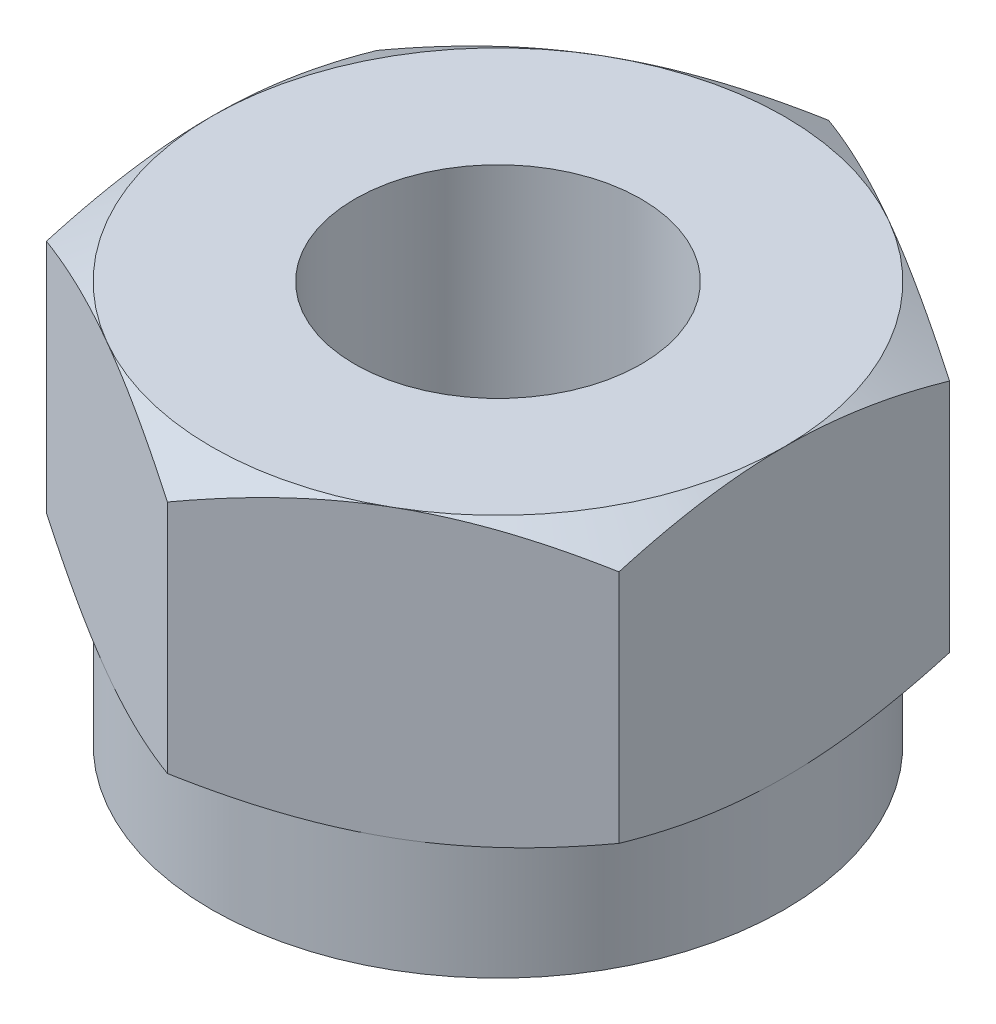
SolidWorks part; units mm, degrees
material "AISI 304"
ref_plane "前视基准面" through (0, 0, 0) normal (0, 0, 1) x (1, 0, 0)
ref_plane "上视基准面" through (0, 0, 0) normal (0, 1, 0) x (1, 0, 0)
ref_plane "右视基准面" through (0, 0, 0) normal (1, 0, 0) x (0, 0, -1)
sketch "草图1" plane through (0, 0, 0) normal (0, 1, 0) x (1, 0, 0)
  line L1 (2, 1.1547) -> (0, 2.3094)
  line L2 (0, 2.3094) -> (-2, 1.1547)
  line L3 (-2, 1.1547) -> (-2, -1.1547)
  line L4 (-2, -1.1547) -> (0, -2.3094)
  line L5 (0, -2.3094) -> (2, -1.1547)
  line L6 (2, -1.1547) -> (2, 1.1547)
  circle A0 centre (0, 0) radius 1
  circle A1 centre (0, 0) radius 2 construction
  dimension "D1" = 2
  dimension "D2" = 4
extrude "凸台-拉伸2" add sketch "草图1" along normal blind 2
cosmetic thread "装饰螺纹线1" parameters "D2"=22
sketch "草图2" plane through (0, 0, 0) normal (0, 0, 1) x (1, 0, 0)
  line L0 (2, 2) -> (3.7321, 2)
  line L1 (3.7321, 2) -> (3.7321, 1)
  line L2 (3.7321, 1) -> (2, 2)
  line L3 (2, 0) -> (3.7321, 0)
  line L4 (3.7321, 0) -> (3.7321, 1)
  line L5 (2, 0) -> (3.7321, 1)
  line L6 (0, 1.9814) -> (0, 2.9288) construction
  dimension "D1" = 30
  dimension "D2" = 30
revolve "切除-旋转1" cut sketch "草图2" angle 360 about L6
sketch "草图3" plane through (0, 0, 0) normal (0, -1, 0) x (1, 0, 0)
  circle A0 centre (0, 0) radius 2
  circle A1 centre (0, 0) radius 1
  dimension "D1" = 2
  dimension "D2" = 4
extrude "凸台-拉伸3" add sketch "草图3" along normal blind 0.8
fillet "圆角1" [suppressed] radius 1
